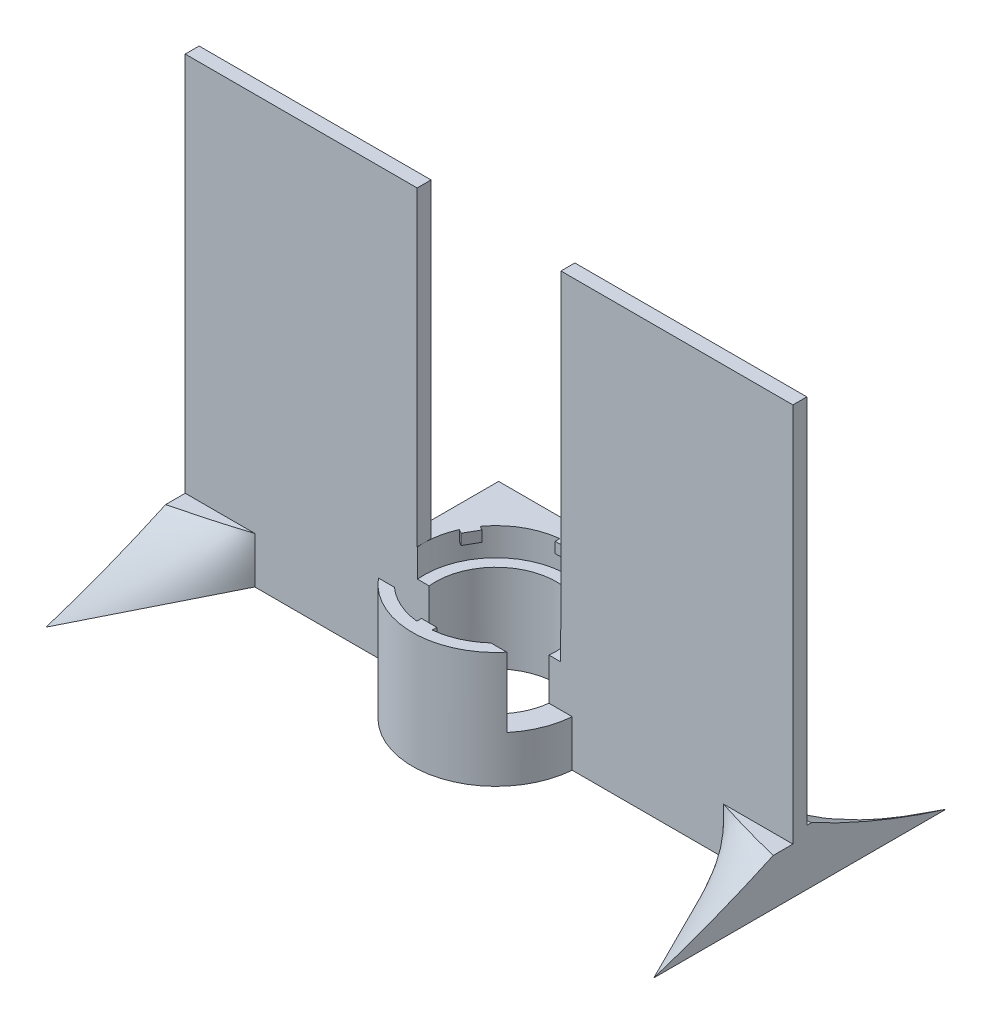
SolidWorks part; units mm, degrees
ref_plane "Front Plane" through (0, 0, 0) normal (0, 0, 1) x (1, 0, 0)
ref_plane "Top Plane" through (0, 0, 0) normal (0, 1, 0) x (1, 0, 0)
ref_plane "Right Plane" through (0, 0, 0) normal (1, 0, 0) x (0, 0, -1)
ref_plane "Plane1" through (15.5, 0, 0) normal (1, 0, 0) x (0, 0, -1)
ref_plane "Plane2" through (120, 0, 0) normal (1, 0, 0) x (0, 0, -1)
sketch "Sketch1" plane through (15.5, 0, 0) normal (1, 0, 0) x (0, 0, -1)
  line L0 (0, 0) -> (0, 12)
  line L1 (0, 55) -> (0, -55) construction
  line L2 (0, 12) -> (0, 92)
  line L3 (0, 92) -> (1.5, 92)
  line L4 (0, 92) -> (-1.5, 92)
  line L6 (1.5, 92) -> (-1.5, 92)
  line L7 (1.5, 92) -> (1.5, 12)
  line L8 (1.5, 12) -> (-1.5, 12)
  line L9 (-1.5, 92) -> (-1.5, 12)
  line L10 (1.5, 12) -> (-1.5, 12)
  line L11 (1.5, 12) -> (1.5, 0)
  line L12 (1.5, 0) -> (-1.5, 0)
  line L13 (-1.5, 12) -> (-1.5, 0)
  point P12 (0, 0)
  dimension "D1" = 80
  dimension "D2" = 3
  dimension "D3" = 12
extrude "Boss-Extrude1" add sketch "Sketch1" along normal blind 50 contours L7 L6 L9 L8
sketch "Sketch5" plane through (65.5, 0, 0) normal (1, 0, 0) x (0, 0, -1)
  line L0 (1.5, 92) -> (1.5, 12) construction
  line L1 (-1.5, 12) -> (2.5, 12)
  line L6 (-31.5, 0) -> (31.5, 0)
  spline S0 degree 2 poles (-1.5, 12) (-16.0718, 4.9063) (-31.5, 0) knots 0 0 0 1 1 1
  spline S1 degree 2 poles (2.5, 12) (16.4462, 4.629) (31.5, 0) knots 0 0 0 1 1 1
  dimension "D2" = 4
  dimension "D3" = 30
  dimension "D1" = 30
sketch "Sketch6" plane through (15.5, 0, 0) normal (-1, 0, 0) x (0, 0, 1)
  line L3 (-1.5, 12) -> (1.5, 12)
  line L4 (-1.5, 12) -> (-1.5, 0)
  line L5 (-1.5, 0) -> (1.5, 0)
  line L6 (1.5, 12) -> (1.5, 0)
  dimension "D1" = 12
ref_plane "Plane3" through (50.5, 0, 0) normal (1, 0, 0) x (0, 0, -1)
sketch "Sketch7" plane through (50.5, 0, 0) normal (1, 0, 0) x (0, 0, -1)
  line L1 (-1.5, 12) -> (1.5, 12)
  line L2 (-1.5, 12) -> (-1.5, 0)
  line L3 (-1.5, 0) -> (1.5, 0)
  line L4 (1.5, 12) -> (1.5, 0)
extrude "Boss-Extrude2" add sketch "Sketch6" against normal up to vertex (35 mm away) contours L6 L5 L4 L3 up to point (50.5, 0, -1.5)
loft "Loft3" add profiles "Sketch7", "Sketch5"
mirror "Mirror3" about plane through (0, 0, 0) normal (1, 0, 0) of bodies 105
sketch "Sketch14" plane through (0, 0, 0) normal (0, 1, 0) x (1, 0, 0)
  line L0 (0, -35.2001) -> (0, 35.2001) construction
  circle A0 centre (0, 0) radius 15.5
  circle A1 centre (0, 0) radius 18
  point P4 (0, 14.8838)
  dimension "D1" = 31
  dimension "D2" = 36
extrude "Boss-Extrude3" add sketch "Sketch14" along normal blind 25
sketch "Sketch15" plane through (0, 25, 0) normal (0, 1, 0) x (1, 0, 0)
  line L0 (-1.65, 15.4119) -> (-1.65, 14.4119)
  line L1 (-1.65, 14.4119) -> (1.65, 14.4119)
  line L2 (1.65, 14.4119) -> (1.65, 15.4119)
  line L3 (0, -34.6501) -> (0, 34.6501) construction
  line L4 (-1.65, 15.4119) -> (0, 16.2514)
  line L5 (0, 16.2514) -> (1.65, 15.4119)
  circle A1 centre (0, 0) radius 15.5 construction
  point P12 (0, 14.4119)
  dimension "D1" = 3.3
  dimension "D2" = 1
extrude "Boss-Extrude4" add sketch "Sketch15" against normal blind 2.3
pattern_circular "CirPattern1" count 6 over 360 about axis through (0, 0, 0) along (0, 1, 0) of "Boss-Extrude4"
sketch "Sketch16" plane through (0, 25, 0) normal (0, 1, 0) x (1, 0, 0)
  line L0 (-18.9374, 1.5) -> (-18.9374, 19.5)
  line L1 (-65.5, 1.5) -> (-15.5, 1.5) construction
  line L2 (-18.9374, 19.5) -> (18.9374, 19.5)
  line L3 (18.9374, 19.5) -> (18.9374, 1.5)
  line L4 (65.5, 1.5) -> (15.5, 1.5) construction
  line L5 (18.9374, 1.5) -> (17.9374, 1.5)
  line L6 (-18.9374, 1.5) -> (-17.9374, 1.5)
  line L7 (0, -34.6501) -> (0, 34.6501) construction
  line L8 (15.5, 1.5) -> (17.9374, 1.5) construction
  arc A0 (17.9374, 1.5) -> (-17.9374, 1.5) centre (0, 0) ccw
  point P1 (0, 19.5)
  dimension "D1" = 1
  dimension "D2" = 18
extrude "Boss-Extrude5" add sketch "Sketch16" against normal up to surface (25 mm away) up to face at (0, 0, 15.5)
sketch "Sketch17" plane through (0, 25, 0) normal (0, 1, 0) x (1, 0, 0)
  circle A0 centre (0, 0) radius 13
  circle A1 centre (0, 0) radius 15.5
  arc A2 (12.5221, 9.1349) -> (1.65, 15.4119) centre (0, 0) ccw construction
  dimension "D1" = 26
extrude "Boss-Extrude6" add sketch "Sketch17" against normal up to surface (19 mm away) from offset 6 up to face at (0, 0, -1.3929) offset against normal yes
sketch "Sketch18" plane through (0, 0, 0) normal (1, 0, 0) x (0, 0, -1)
  line L1 (-1.5, 25) -> (-11.5, 25)
  line L2 (-1.5, 25) -> (-1.5, 10)
  line L3 (-1.5, 10) -> (-11.5, 10)
  line L4 (-11.5, 25) -> (-11.5, 10)
  dimension "D1" = 10
  dimension "D2" = 15
extrude "Cut-Extrude1" cut sketch "Sketch18" against normal through all both and the other way through all
equation "\"D1@Sketch5\"=\"D3@Sketch5\""
